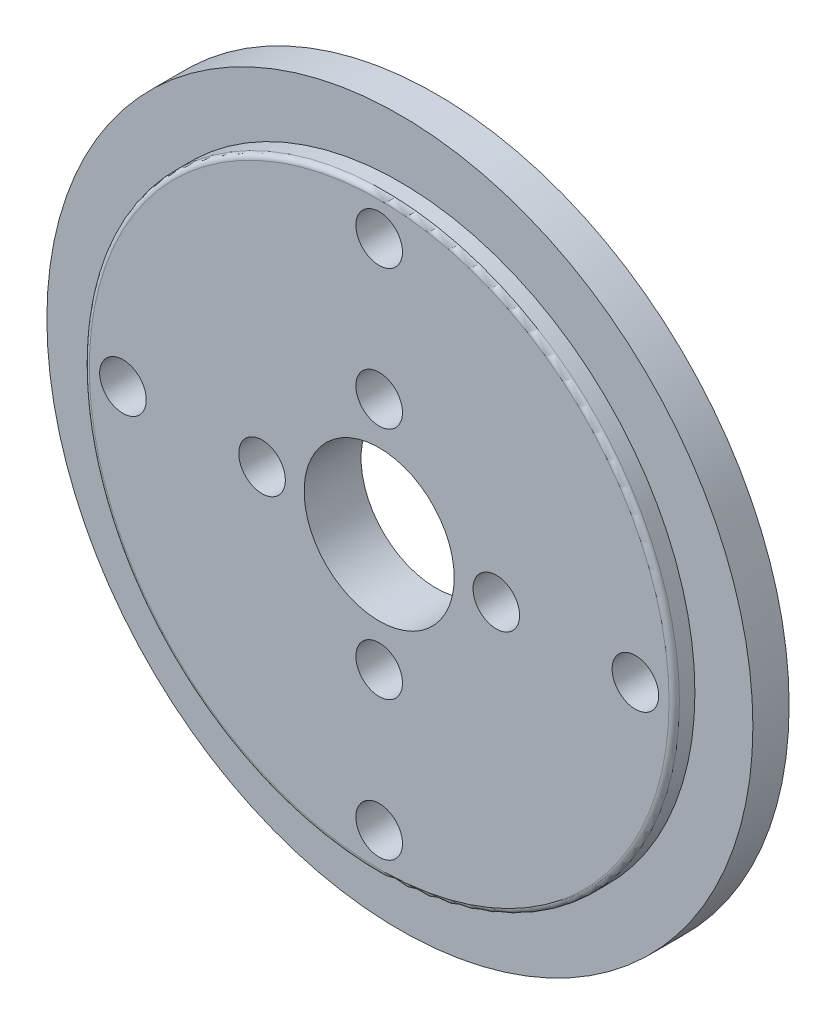
SolidWorks part; units mm, degrees
ref_plane "Front Plane" through (0, 0, 0) normal (0, 0, 1) x (1, 0, 0)
ref_plane "Top Plane" through (0, 0, 0) normal (0, 1, 0) x (1, 0, 0)
ref_plane "Right Plane" through (0, 0, 0) normal (1, 0, 0) x (0, 0, -1)
sketch "Sketch1" plane through (0, 0, 0) normal (0, 0, 1) x (1, 0, 0)
  circle A0 centre (0, 0) radius 34.1
  dimension "D1" = 68.2
extrude "Boss-Extrude1" add sketch "Sketch1" along normal mid plane 3.5
sketch "Sketch4" plane through (0, 0, 1.75) normal (0, 0, 1) x (1, 0, 0)
  circle A0 centre (0, 0) radius 28.5
  dimension "D1" = 57
extrude "Boss-Extrude2" add sketch "Sketch4" along normal blind 2
sketch "Sketch3" plane through (0, 0, 1.75) normal (0, 0, 1) x (1, 0, 0)
  line L0 (0, 0) -> (0, 24.75) construction
  circle A0 centre (0, 24.75) radius 2.25
  circle A8 centre (0, 0) radius 11.3137 construction
  circle A9 centre (0, 11.3137) radius 2.25
  circle A10 centre (24.75, 0) radius 2.25
  circle A11 centre (11.3137, 0) radius 2.25
  circle A12 centre (0, -24.75) radius 2.25
  circle A13 centre (0, -11.3137) radius 2.25
  circle A14 centre (-24.75, 0) radius 2.25
  circle A15 centre (-11.3137, 0) radius 2.25
  point P21 (0, 0)
  dimension "D2" = 4.5
  dimension "D3" = 22.6274
  dimension "D4" = 4.5
  dimension "D5" = 4
  dimension "D1" = 24.75
extrude "Cut-Extrude2" cut sketch "Sketch3" against normal through all both and the other way through all
sketch "Sketch2" plane through (0, 0, 1.75) normal (0, 0, 1) x (1, 0, 0)
  circle A0 centre (0, 0) radius 7.25
  dimension "D1" = 14.5
extrude "Cut-Extrude1" cut sketch "Sketch2" along normal through all both and the other way through all
fillet "Fillet1" radius 0.5 1 edges at (28.5, 0, 3.75)
